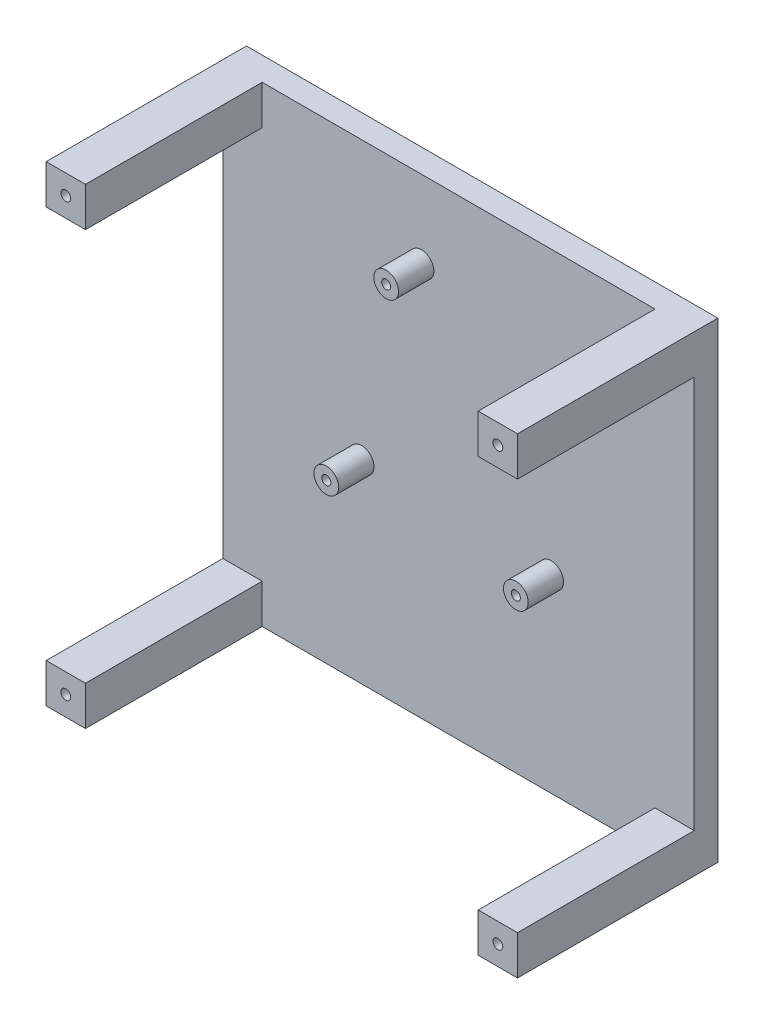
SolidWorks part; units mm, degrees
ref_plane "Front Plane" through (0, 0, 0) normal (1, 0, 0) x (0, 1, 0)
ref_plane "Top Plane" through (0, 0, 0) normal (0, 0, 1) x (0, 1, 0)
ref_plane "Right Plane" through (0, 0, 0) normal (0, 1, 0) x (-1, 0, 0)
sketch "Sketch1" plane through (0, 0, 0) normal (0, 0, 1) x (0, 1, 0)
  line L1 (-60, -60) -> (60, -60)
  line L2 (-60, -60) -> (-60, 60)
  line L3 (-60, 60) -> (60, 60)
  line L4 (60, -60) -> (60, 60)
  line L5 (-60, -60) -> (60, 60) construction
  line L6 (-60, 60) -> (60, -60) construction
  point P0 (0, 0)
  dimension "D1" = 120
  dimension "D2" = 120
extrude "Boss-Extrude1" add sketch "Sketch1" along normal blind 6
sketch "Sketch2" plane through (0, 0, 6) normal (0, 0, 1) x (1, 0, 0)
  line L1 (-60, 60) -> (-50, 60)
  line L2 (-60, 60) -> (-60, 50)
  line L3 (-60, 50) -> (-50, 50)
  line L4 (-50, 60) -> (-50, 50)
  line L5 (0, -3.3) -> (0, 3.3) construction
  line L6 (50, 60) -> (50, 50)
  line L7 (60, 50) -> (50, 50)
  line L8 (60, 60) -> (60, 50)
  line L9 (60, 60) -> (50, 60)
  line L10 (3.3, 0) -> (-3.3, 0) construction
  line L11 (60, -60) -> (50, -60)
  line L12 (60, -60) -> (60, -50)
  line L13 (60, -50) -> (50, -50)
  line L14 (50, -60) -> (50, -50)
  line L15 (-50, -60) -> (-50, -50)
  line L16 (-60, -50) -> (-50, -50)
  line L17 (-60, -60) -> (-60, -50)
  line L18 (-60, -60) -> (-50, -60)
  dimension "D1" = 10
  dimension "D2" = 10
extrude "Boss-Extrude2" add sketch "Sketch2" along normal blind 45
sketch "Sketch4" plane through (0, 0, 51) normal (0, 0, 1) x (1, 0, 0)
  line L0 (-50, 60) -> (-60, 60) construction
  line L1 (-60, 60) -> (-60, 50) construction
  circle A0 centre (-55, 55) radius 1.25
  dimension "D1" = 2.5
  dimension "D2" = 5
  dimension "D3" = 5
extrude "Cut-Extrude1" cut sketch "Sketch4" against normal blind 14
mirror "Mirror1" about plane through (0, 0, 0) normal (0, 1, 0) of "Cut-Extrude1" second plane through (0, 0, 0) second plane normal (1, 0, 0)
sketch "Sketch5" plane through (0, 0, 6) normal (0, 0, 1) x (1, 0, 0)
  line L0 (-14.0506, 40.7161) -> (-33.5506, 40.7161)
  line L1 (-35.5506, 38.7161) -> (-35.5506, -14.3239)
  line L2 (-35.5506, -14.3239) -> (-19.5506, -14.3239)
  line L3 (-19.5506, -15.3239) -> (-35.5506, -15.3239)
  line L4 (-35.5506, -15.3239) -> (-35.5506, -37.7839)
  line L5 (-33.5506, -39.7839) -> (32.4494, -39.7839)
  line L6 (34.4494, -37.7839) -> (34.4494, -15.3239)
  line L7 (34.4494, -15.3239) -> (18.9494, -15.3239)
  line L8 (18.9494, -14.3239) -> (34.4494, -14.3239)
  line L9 (34.4494, -14.3239) -> (34.4494, 38.7161)
  line L10 (32.4494, 40.7161) -> (22.9494, 40.7161)
  line L11 (22.9494, 40.7161) -> (20.9494, 42.7161)
  line L12 (20.9494, 42.7161) -> (-12.0506, 42.7161)
  line L13 (-12.0506, 42.7161) -> (-14.0506, 40.7161)
  arc A3 (-33.5506, 40.7161) -> (-35.5506, 38.7161) centre (-33.5506, 38.7161) ccw
  arc A4 (-19.5506, -15.3239) -> (-19.5506, -14.3239) centre (-19.5506, -14.8239) ccw
  arc A5 (-35.5506, -37.7839) -> (-33.5506, -39.7839) centre (-33.5506, -37.7839) ccw
  arc A6 (32.4494, -39.7839) -> (34.4494, -37.7839) centre (32.4494, -37.7839) ccw
  arc A7 (18.9494, -14.3239) -> (18.9494, -15.3239) centre (18.9494, -14.8239) ccw
  arc A8 (34.4494, 38.7161) -> (32.4494, 40.7161) centre (32.4494, 38.7161) ccw
  circle A12 centre (-9.4406, 40.2161) radius 3.15
  circle A13 centre (-24.6806, -10.5839) radius 3.15
  circle A14 centre (23.5794, -11.8539) radius 3.15
  dimension "D1" = 6.3
  dimension "D2" = 6.3
  dimension "D3" = 6.3
extrude "Boss-Extrude4" add sketch "Sketch5" along normal blind 9
ref_plane "Plane2" through (0, 0, 15) normal (0, 0, 1) x (0, -1, 0)
sketch "Sketch7" plane through (0, 0, 15) normal (0, 0, 1) x (0, -1, 0)
  circle A0 centre (-40.2161, -9.4406) radius 1.15
  circle A1 centre (11.8539, 23.5794) radius 1.15
  circle A2 centre (10.5839, -24.6806) radius 1.15
  dimension "D1" = 2.3
  dimension "D2" = 2.3
  dimension "D3" = 2.3
extrude "Cut-Extrude2" cut sketch "Sketch7" against normal blind 9
